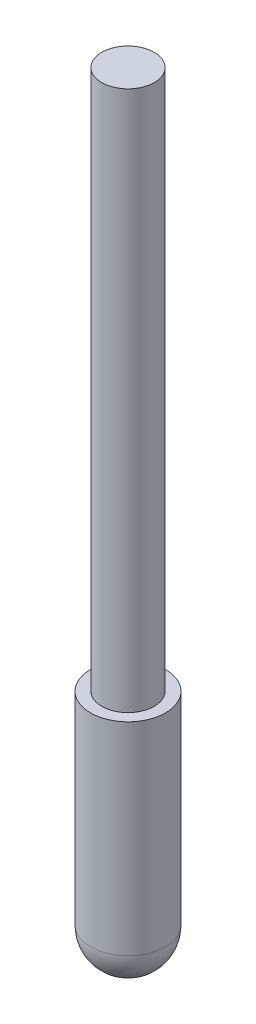
SolidWorks part; units mm, degrees
material "PVC Rigid"
ref_plane "Front Plane" through (0, 0, 0) normal (0, 0, 1) x (1, 0, 0)
ref_plane "Top Plane" through (0, 0, 0) normal (0, 1, 0) x (1, 0, 0)
ref_plane "Right Plane" through (0, 0, 0) normal (1, 0, 0) x (0, 0, -1)
sketch "Sketch1" plane through (0, 0, 0) normal (0, 1, 0) x (1, 0, 0)
  circle A0 centre (0, 0) radius 1.75
  dimension "D1" = 3.5
extrude "Boss-Extrude1" add sketch "Sketch1" along normal blind 36
sketch "Sketch2" plane through (0, 0, 0) normal (0, -1, 0) x (1, 0, 0)
  circle A0 centre (0, 0) radius 2.5
  dimension "D1" = 5
extrude "Boss-Extrude2" add sketch "Sketch2" along normal blind 16
fillet "Fillet1" radius 2.5 1 edges at (0, -16, -2.5)
